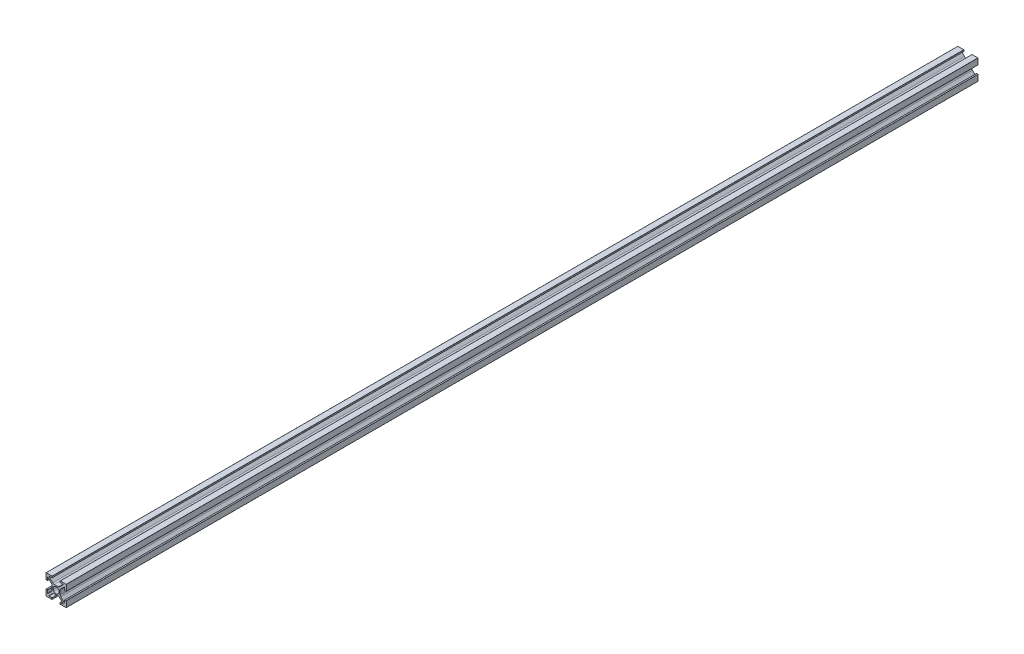
SolidWorks part; units mm, degrees
material "6061-T6 (SS)"
ref_plane "Front Plane" through (0, 0, 0) normal (0, 0, 1) x (1, 0, 0)
ref_plane "Top Plane" through (0, 0, 0) normal (0, 1, 0) x (1, 0, 0)
ref_plane "Right Plane" through (0, 0, 0) normal (1, 0, 0) x (0, 0, -1)
ref_plane "Plane1" through (0, 0, 60) normal (0, 0, 1) x (1, 0, 0)
sketch "Sketch1" plane through (0, 0, 60) normal (0, 0, 1) x (1, 0, 0)
  line L0 (18.5, 17.0086) -> (18.5, 14.1)
  line L1 (18.6, 14) -> (19.9, 14)
  line L2 (20, 14.1) -> (20, 19.9)
  line L3 (19.9, 20) -> (14.1, 20)
  line L4 (14, 19.9) -> (14, 18.6)
  line L5 (14.1, 18.5) -> (17.0086, 18.5)
  line L6 (17.0793, 18.3293) -> (13.3358, 14.5858)
  line L7 (11.9216, 14) -> (8.0784, 14)
  line L8 (6.6642, 14.5858) -> (2.9207, 18.3293)
  line L9 (2.9914, 18.5) -> (5.9, 18.5)
  line L10 (6, 18.6) -> (6, 19.9)
  line L11 (5.9, 20) -> (0.1, 20)
  line L12 (0, 19.9) -> (0, 14.1)
  line L13 (0.1, 14) -> (1.4, 14)
  line L14 (1.5, 14.1) -> (1.5, 17.0086)
  line L15 (1.6707, 17.0793) -> (5.4142, 13.3358)
  line L16 (6, 11.9216) -> (6, 8.0784)
  line L17 (5.4142, 6.6642) -> (1.6707, 2.9207)
  line L18 (1.5, 2.9914) -> (1.5, 5.9)
  line L19 (1.4, 6) -> (0.1, 6)
  line L20 (0, 5.9) -> (0, 0.1)
  line L21 (0.1, 0) -> (5.9, 0)
  line L22 (6, 0.1) -> (6, 1.4)
  line L23 (5.9, 1.5) -> (2.9914, 1.5)
  line L24 (2.9207, 1.6707) -> (6.6642, 5.4142)
  line L25 (8.0784, 6) -> (11.9216, 6)
  line L26 (13.3358, 5.4142) -> (17.0793, 1.6707)
  line L27 (17.0086, 1.5) -> (14.1, 1.5)
  line L28 (14, 1.4) -> (14, 0.1)
  line L29 (14.1, 0) -> (19.9, 0)
  line L30 (20, 0.1) -> (20, 5.9)
  line L31 (19.9, 6) -> (18.6, 6)
  line L32 (18.5, 5.9) -> (18.5, 2.9914)
  line L33 (18.3293, 2.9207) -> (14.5858, 6.6642)
  line L34 (14, 8.0784) -> (14, 11.9216)
  line L35 (14.5858, 13.3358) -> (18.3293, 17.0793)
  circle A0 centre (10, 10) radius 3
  arc A1 (18.3293, 17.0793) -> (18.5, 17.0086) centre (18.4, 17.0086) cw
  arc A2 (18.5, 14.1) -> (18.6, 14) centre (18.6, 14.1) ccw
  arc A3 (19.9, 14) -> (20, 14.1) centre (19.9, 14.1) ccw
  arc A4 (20, 19.9) -> (19.9, 20) centre (19.9, 19.9) ccw
  arc A5 (14.1, 20) -> (14, 19.9) centre (14.1, 19.9) ccw
  arc A6 (14, 18.6) -> (14.1, 18.5) centre (14.1, 18.6) ccw
  arc A7 (17.0086, 18.5) -> (17.0793, 18.3293) centre (17.0086, 18.4) cw
  arc A8 (13.3358, 14.5858) -> (11.9216, 14) centre (11.9216, 16) cw
  arc A9 (8.0784, 14) -> (6.6642, 14.5858) centre (8.0784, 16) cw
  arc A10 (2.9207, 18.3293) -> (2.9914, 18.5) centre (2.9914, 18.4) cw
  arc A11 (5.9, 18.5) -> (6, 18.6) centre (5.9, 18.6) ccw
  arc A12 (6, 19.9) -> (5.9, 20) centre (5.9, 19.9) ccw
  arc A13 (0.1, 20) -> (0, 19.9) centre (0.1, 19.9) ccw
  arc A14 (0, 14.1) -> (0.1, 14) centre (0.1, 14.1) ccw
  arc A15 (1.4, 14) -> (1.5, 14.1) centre (1.4, 14.1) ccw
  arc A16 (1.5, 17.0086) -> (1.6707, 17.0793) centre (1.6, 17.0086) cw
  arc A17 (5.4142, 13.3358) -> (6, 11.9216) centre (4, 11.9216) cw
  arc A18 (6, 8.0784) -> (5.4142, 6.6642) centre (4, 8.0784) cw
  arc A19 (1.6707, 2.9207) -> (1.5, 2.9914) centre (1.6, 2.9914) cw
  arc A20 (1.5, 5.9) -> (1.4, 6) centre (1.4, 5.9) ccw
  arc A21 (0.1, 6) -> (0, 5.9) centre (0.1, 5.9) ccw
  arc A22 (0, 0.1) -> (0.1, 0) centre (0.1, 0.1) ccw
  arc A23 (5.9, 0) -> (6, 0.1) centre (5.9, 0.1) ccw
  arc A24 (6, 1.4) -> (5.9, 1.5) centre (5.9, 1.4) ccw
  arc A25 (2.9914, 1.5) -> (2.9207, 1.6707) centre (2.9914, 1.6) cw
  arc A26 (6.6642, 5.4142) -> (8.0784, 6) centre (8.0784, 4) cw
  arc A27 (11.9216, 6) -> (13.3358, 5.4142) centre (11.9216, 4) cw
  arc A28 (17.0793, 1.6707) -> (17.0086, 1.5) centre (17.0086, 1.6) cw
  arc A29 (14.1, 1.5) -> (14, 1.4) centre (14.1, 1.4) ccw
  arc A30 (14, 0.1) -> (14.1, 0) centre (14.1, 0.1) ccw
  arc A31 (19.9, 0) -> (20, 0.1) centre (19.9, 0.1) ccw
  arc A32 (20, 5.9) -> (19.9, 6) centre (19.9, 5.9) ccw
  arc A33 (18.6, 6) -> (18.5, 5.9) centre (18.6, 5.9) ccw
  arc A34 (18.5, 2.9914) -> (18.3293, 2.9207) centre (18.4, 2.9914) cw
  arc A35 (14.5858, 6.6642) -> (14, 8.0784) centre (16, 8.0784) cw
  arc A36 (14, 11.9216) -> (14.5858, 13.3358) centre (16, 11.9216) cw
extrude "Boss-Extrude2" add sketch "Sketch1" along normal blind 900
ref_plane "Plane2" through (11.9216, 14, 960) normal (-1, 0, 0) x (0, 0, 1)
sketch "Sketch3" plane through (0, 0, 960) normal (0, 0, 1) x (1, 0, 0)
  line L0 (10, 6.4152) -> (10, 21.5848) construction
  point P3 (10, 14)
sketch "Sketch5" plane through (0, 0, 60) normal (0, 0, -1) x (-1, 0, 0)
  line L0 (-10, -0.8966) -> (-10, 20.8966) construction
  point P4 (-10, 10)
